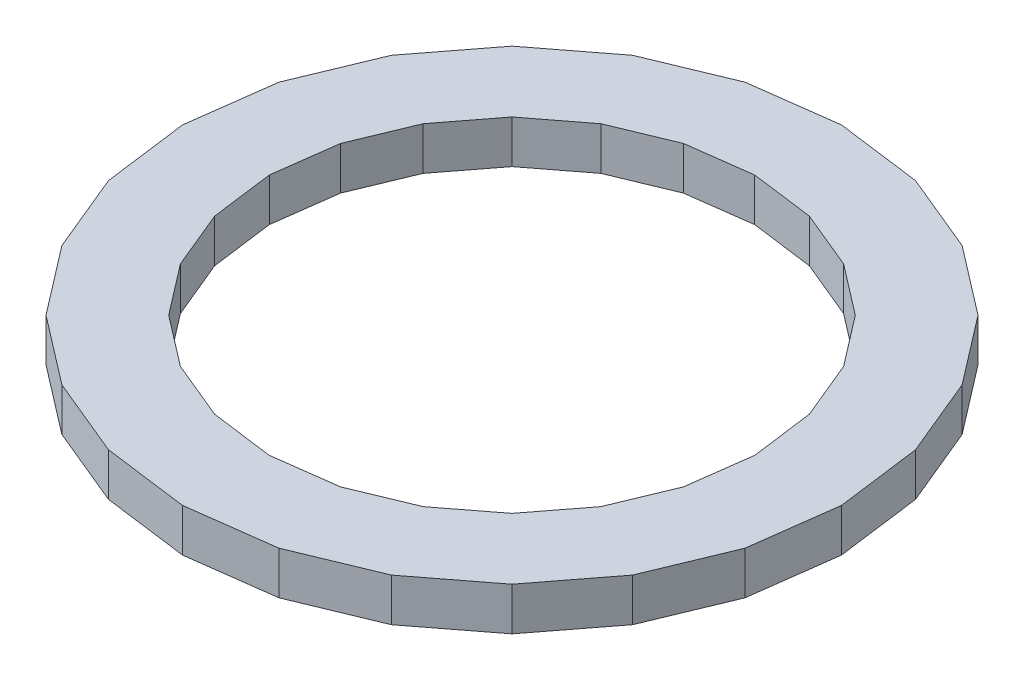
SolidWorks part; units mm, degrees
ref_plane "Front Plane" through (0, 0, 0) normal (0, 0, 1) x (1, 0, 0)
ref_plane "Top Plane" through (0, 0, 0) normal (0, 1, 0) x (1, 0, 0)
ref_plane "Right Plane" through (0, 0, 0) normal (1, 0, 0) x (0, 0, -1)
sketch "Sketch3" plane through (0, 0, 0) normal (0, 1, 0) x (1, 0, 0)
  line L0 (0, 0) -> (-107.519, 0) construction
  line L1 (-145.9477, 0) -> (-140.9747, -37.774)
  line L2 (-140.9747, -37.774) -> (-126.3944, -72.9739)
  line L3 (-126.3944, -72.9739) -> (-103.2006, -103.2006)
  line L4 (-103.2006, -103.2006) -> (-72.9739, -126.3944)
  line L5 (-72.9739, -126.3944) -> (-37.774, -140.9747)
  line L6 (-37.774, -140.9747) -> (0, -145.9477)
  line L7 (0, -145.9477) -> (37.774, -140.9747)
  line L8 (37.774, -140.9747) -> (72.9739, -126.3944)
  line L9 (72.9739, -126.3944) -> (103.2006, -103.2006)
  line L10 (103.2006, -103.2006) -> (126.3944, -72.9739)
  line L11 (126.3944, -72.9739) -> (140.9747, -37.774)
  line L12 (140.9747, -37.774) -> (145.9477, 0)
  line L13 (145.9477, 0) -> (140.9747, 37.774)
  line L14 (140.9747, 37.774) -> (126.3944, 72.9739)
  line L15 (126.3944, 72.9739) -> (103.2006, 103.2006)
  line L16 (103.2006, 103.2006) -> (72.9739, 126.3944)
  line L17 (72.9739, 126.3944) -> (37.774, 140.9747)
  line L18 (37.774, 140.9747) -> (0, 145.9477)
  line L19 (0, 145.9477) -> (-37.774, 140.9747)
  line L20 (-37.774, 140.9747) -> (-72.9739, 126.3944)
  line L21 (-72.9739, 126.3944) -> (-103.2006, 103.2006)
  line L22 (-103.2006, 103.2006) -> (-126.3944, 72.9739)
  line L23 (-126.3944, 72.9739) -> (-140.9747, 37.774)
  line L24 (-140.9747, 37.774) -> (-145.9477, 0)
  line L25 (-107.519, 0) -> (-103.8553, -27.828)
  line L26 (-103.8553, -27.828) -> (-93.1141, -53.7595)
  line L27 (-93.1141, -53.7595) -> (-76.0274, -76.0274)
  line L28 (-76.0274, -76.0274) -> (-53.7595, -93.1141)
  line L29 (-53.7595, -93.1141) -> (-27.828, -103.8553)
  line L30 (-27.828, -103.8553) -> (0, -107.519)
  line L31 (0, -107.519) -> (27.828, -103.8553)
  line L32 (27.828, -103.8553) -> (53.7595, -93.1141)
  line L33 (53.7595, -93.1141) -> (76.0274, -76.0274)
  line L34 (76.0274, -76.0274) -> (93.1141, -53.7595)
  line L35 (93.1141, -53.7595) -> (103.8553, -27.828)
  line L36 (103.8553, -27.828) -> (107.519, 0)
  line L37 (107.519, 0) -> (103.8553, 27.828)
  line L38 (103.8553, 27.828) -> (93.1141, 53.7595)
  line L39 (93.1141, 53.7595) -> (76.0274, 76.0274)
  line L40 (76.0274, 76.0274) -> (53.7595, 93.1141)
  line L41 (53.7595, 93.1141) -> (27.828, 103.8553)
  line L42 (27.828, 103.8553) -> (0, 107.519)
  line L43 (0, 107.519) -> (-27.828, 103.8553)
  line L44 (-27.828, 103.8553) -> (-53.7595, 93.1141)
  line L45 (-53.7595, 93.1141) -> (-76.0274, 76.0274)
  line L46 (-76.0274, 76.0274) -> (-93.1141, 53.7595)
  line L47 (-93.1141, 53.7595) -> (-103.8553, 27.828)
  line L48 (-103.8553, 27.828) -> (-107.519, 0)
  line L49 (-145.9477, 0) -> (-107.519, 0) construction
  circle A0 centre (0, 0) radius 144.6991 construction
  circle A1 centre (0, 0) radius 106.5991 construction
  dimension "D1" = 38.1
  dimension "D2" = 38.1
extrude "Boss-Extrude3" add sketch "Sketch3" along normal blind 19.05
